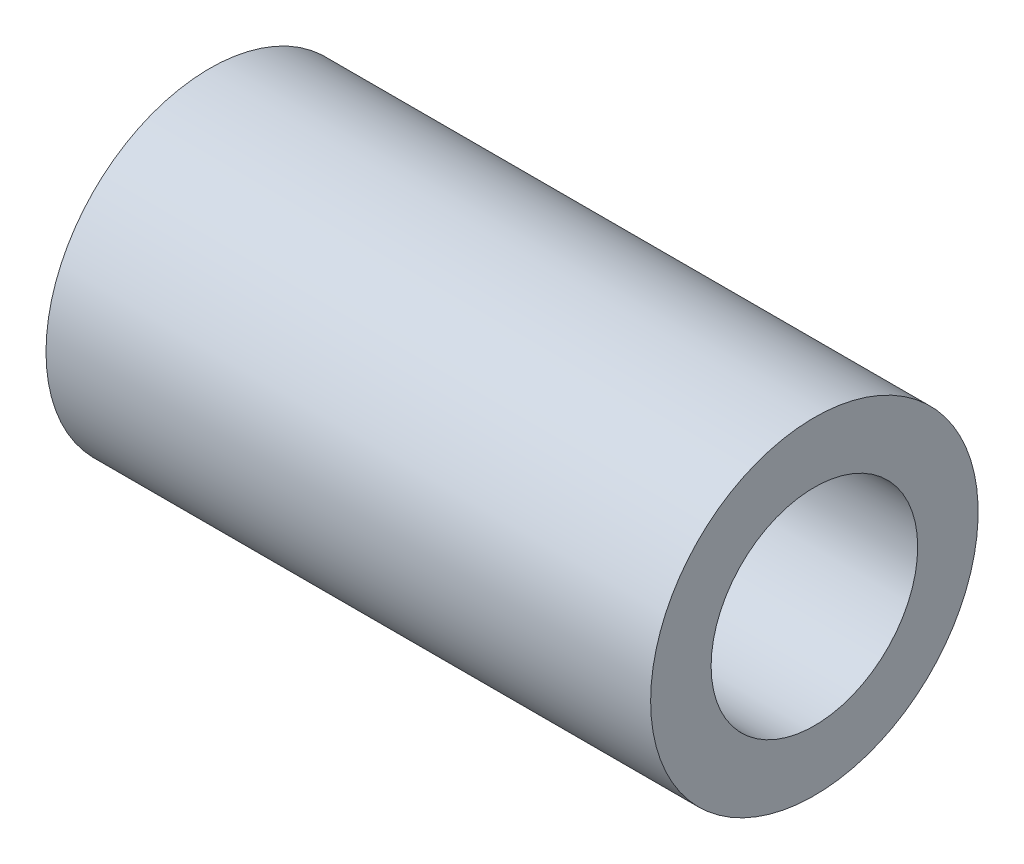
SolidWorks part; units mm, degrees
material "AISI 1020"
ref_plane "Plano superior" through (0, 0, 0) normal (0, 0, 1) x (1, 0, 0)
ref_plane "Plano frontal" through (0, 0, 0) normal (0, 1, 0) x (1, 0, 0)
ref_plane "Plano direito" through (0, 0, 0) normal (1, 0, 0) x (0, 0, -1)
sketch "Esboço1" plane through (0, 0, 0) normal (0, 1, 0) x (1, 0, 0)
  line L1 (12, 2.05) -> (12, 3.25)
  line L2 (12, 3.25) -> (0, 3.25)
  line L3 (0, 3.25) -> (0, 2.35)
  line L4 (0, 2.35) -> (8, 2.35)
  line L5 (8, 2.35) -> (8, 2.05)
  line L6 (8, 2.05) -> (12, 2.05)
  line L7 (0, 0) -> (12.7601, 0) construction
  dimension "D1" = 3.25
  dimension "D2" = 12
  dimension "D3" = 4
  dimension "D4" = 2.35
  dimension "D5" = 2.05
  dimension "D6" = 8
revolve "Revolução1" add sketch "Esboço1" angle 360 about L7
